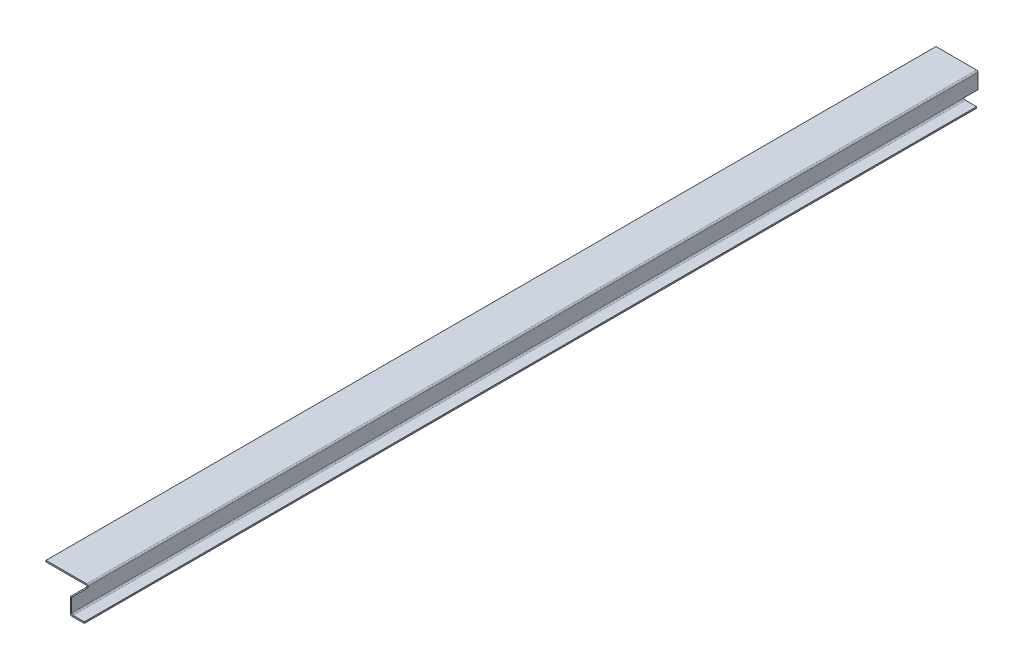
SolidWorks part; units mm, degrees
ref_plane "Front Plane" through (0, 0, 0) normal (0, 0, 1) x (1, 0, 0)
ref_plane "Top Plane" through (0, 0, 0) normal (0, 1, 0) x (1, 0, 0)
ref_plane "Right Plane" through (0, 0, 0) normal (1, 0, 0) x (0, 0, -1)
sketch "Sketch1" plane through (0, 0, 0) normal (0, 0, 1) x (1, 0, 0)
  line L0 (0, 0) -> (87, 0)
  line L1 (87, 0) -> (87, -38)
  line L2 (87, -38) -> (117, -38)
  line L3 (0, 3) -> (90, 3)
  line L4 (90, 3) -> (90, -35)
  line L5 (90, -35) -> (117, -35)
  line L6 (0, 3) -> (0, 0)
  line L7 (117, -35) -> (117, -38)
  dimension "D1" = 3
  dimension "D2" = 90
  dimension "D3" = 27
  dimension "D4" = 38
extrude "Boss-Extrude1" add sketch "Sketch1" along normal blind 1940
fillet "Fillet1" radius 3 4 edges at (87, -38, 970) (87, 0, 970) (90, -35, 970) (90, 3, 970)
sketch "Sketch2" plane through (0, 3, 0) normal (0, 1, 0) x (1, 0, 0)
  line L3 (0, -1940) -> (0, -1905)
  line L6 (0, -1940) -> (0, 0) construction
  line L14 (0, -1905) -> (90, -1905)
  line L15 (90, -1940) -> (90, 0) construction
  line L16 (90, -1905) -> (90, -1940)
  line L17 (90, -1940) -> (0, -1940)
  line L18 (87, 0) -> (0, 0) construction
  dimension "D1" = 1905
sketch "Sketch3" plane through (0, -38, 0) normal (0, -1, 0) x (1, 0, 0)
  line L1 (87, 0) -> (117, 0)
  line L3 (117, 0) -> (117, 30)
  line L5 (117, 1940) -> (117, 0) construction
  line L13 (117, 30) -> (87, 30)
  line L14 (87, 0) -> (87, 1940) construction
  line L15 (87, 30) -> (87, 0)
  dimension "D1" = 30
extrude "Cut-Extrude3" cut sketch "Sketch2" against normal blind 6
extrude "Cut-Extrude4" cut sketch "Sketch3" against normal blind 6
equation "\"D1@Sketch2\"= \"indoorHeight\" + \"indoorHeight_para\" - 90 + 30"
equation "\"CarBeamWidth\"=700.0"
equation "\"WheelWidth\"=650.0"
equation "\"Wheel_FrontBoxDistance\"=1390.0"
equation "\"MetalSheet_3mm_length\"=5030.0"
equation "\"MetalSheet_3mm_width\"=1923.0"
equation "\"MetalSheet_3mm_FloorCut_L_length\"=1764.0"
equation "\"MetalSheet_3mm_FloorCut_L_disdance\"=1665.0"
equation "\"MetalSheet_3mm_FloorCut_R_length\"=1764.0"
equation "\"MetalSheet_3mm_FloorCut_R_disdance\"=1665.0"
equation "\"indoorHeight\"=1940.0"
equation "\"haveDoor_R\"=1"
equation "\"side_door_bottom_R_3mm_length\"=1934.0"
equation "\"1Bar_Side_RF_3mm_length\"=1493.0"
equation "\"1Bar_Side_RB_3mm_length\"=1493.0"
equation "\"DoorSeparator_RF_3mm_withHinge_toFrontDistance\"=1673.0"
equation "\"DoorSeparator_RF_3mm_withHinge_exist\"=1"
equation "\"DoorSeparator_RB_3mm_withHinge_toFrontDistance\"=3427.0"
equation "\"DoorSeparator_RB_3mm_withHinge_exist\"=1"
equation "\"Door_R1_L_open_Single_toFrontDistance\"=2547.5"
equation "\"Door_R1_L_open_Single_exist\"=1"
equation "\"Door_R1_R_open_Single_toFrontDistance\"=3422.0"
equation "\"Door_R1_R_open_Single_exist\"=1"
equation "\"x\"=66.0"
equation "\"da\"=62.0"
equation "\"SquareTube_length\"=1923.0"
equation "\"channelSteel_length\"=5030.0"
equation "\"SquareTube_inFront_AvgDistance\"=285.0"
equation "\"SquareTube_inFront_TotalCount\"=5"
equation "\"SquareTube_inFront1_cutDepth50_R\"=0.5"
equation "\"SquareTube_inFront1_cutDepth50_L\"=0.5"
equation "\"SquareTube_inFront2_cutDepth50_R\"=0.5"
equation "\"SquareTube_inFront2_cutDepth50_L\"=0.5"
equation "\"SquareTube_inFront3_cutDepth50_R\"=0.5"
equation "\"SquareTube_inFront3_cutDepth50_L\"=0.5"
equation "\"SquareTube_inFront4_cutDepth50_R\"=0.5"
equation "\"SquareTube_inFront4_cutDepth50_L\"=0.5"
equation "\"SquareTube_inFront5_cutDepth50_R\"=50"
equation "\"SquareTube_inFront5_cutDepth50_L\"=50"
equation "\"SquareTube_inFront6_cutDepth50_R\"=50"
equation "\"SquareTube_inFront6_cutDepth50_L\"=50"
equation "\"SquareTube_inFront7_cutDepth50_R\"=50"
equation "\"SquareTube_inFront7_cutDepth50_L\"=50"
equation "\"SquareTube_inFront8_cutDepth50_R\"=50"
equation "\"SquareTube_inFront8_cutDepth50_L\"=50"
equation "\"SquareTube_inFront9_cutDepth50_R\"=50"
equation "\"SquareTube_inFront9_cutDepth50_L\"=50"
equation "\"SquareTube_inFront10_cutDepth50_R\"=50"
equation "\"SquareTube_inFront10_cutDepth50_L\"=50"
equation "\"SquareTube_inFront11_cutDepth50_R\"=50"
equation "\"SquareTube_inFront11_cutDepth50_L\"=50"
equation "\"SquareTube_inFront12_cutDepth50_R\"=50"
equation "\"SquareTube_inFront12_cutDepth50_L\"=50"
equation "\"SquareTube_inFront13_cutDepth50_R\"=50"
equation "\"SquareTube_inFront13_cutDepth50_L\"=50"
equation "\"SquareTube_inFront14_cutDepth50_R\"=50"
equation "\"SquareTube_inFront14_cutDepth50_L\"=50"
equation "\"SquareTube_inBack_AvgDistance\"=333.125"
equation "\"SquareTube_inBack_TotalCount\"=9"
equation "\"SquareTube_inBack1_cutDepth50_R\"=50"
equation "\"SquareTube_inBack1_cutDepth50_L\"=50"
equation "\"SquareTube_inBack2_cutDepth50_R\"=50"
equation "\"SquareTube_inBack2_cutDepth50_L\"=50"
equation "\"SquareTube_inBack3_cutDepth50_R\"=50"
equation "\"SquareTube_inBack3_cutDepth50_L\"=50"
equation "\"SquareTube_inBack4_cutDepth50_R\"=50"
equation "\"SquareTube_inBack4_cutDepth50_L\"=50"
equation "\"SquareTube_inBack5_cutDepth50_R\"=50"
equation "\"SquareTube_inBack5_cutDepth50_L\"=50"
equation "\"SquareTube_inBack6_cutDepth50_R\"=0.5"
equation "\"SquareTube_inBack6_cutDepth50_L\"=0.5"
equation "\"SquareTube_inBack7_cutDepth50_R\"=0.5"
equation "\"SquareTube_inBack7_cutDepth50_L\"=0.5"
equation "\"SquareTube_inBack8_cutDepth50_R\"=0.5"
equation "\"SquareTube_inBack8_cutDepth50_L\"=0.5"
equation "\"D1@Boss-Extrude1\"=\"indoorHeight\""
equation "\"indoorHeight_para\"=25.0"
